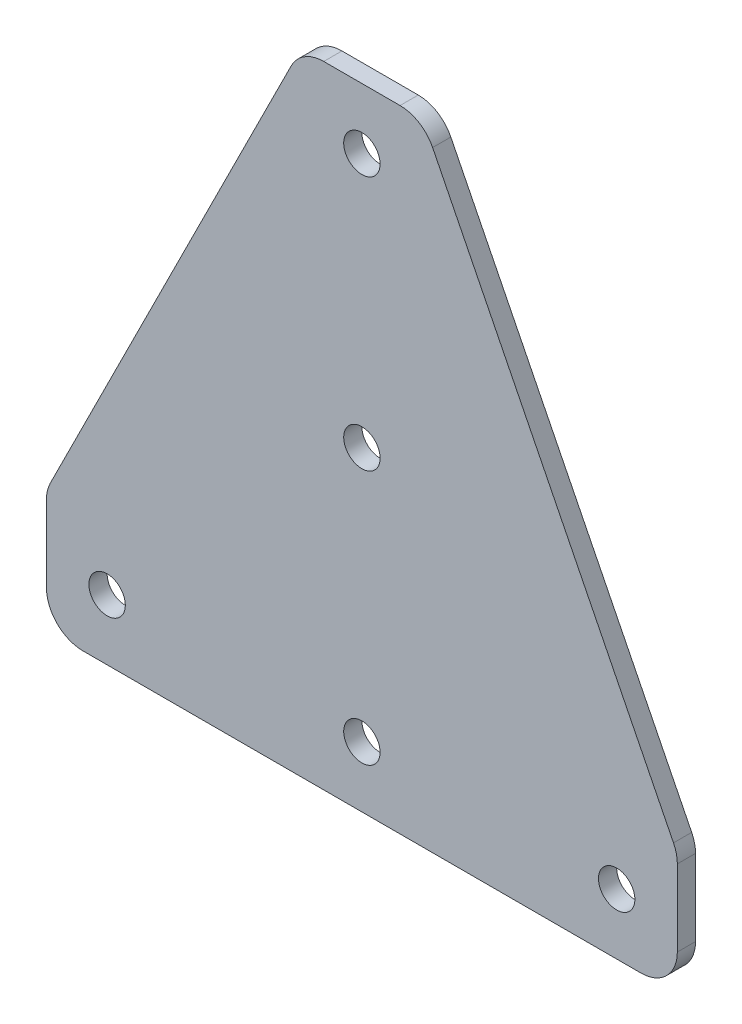
SolidWorks part; units mm, degrees
ref_plane "Plan de face" through (0, 0, 0) normal (0, 0, 1) x (1, 0, 0)
ref_plane "Plan de dessus" through (0, 0, 0) normal (0, 1, 0) x (1, 0, 0)
ref_plane "Plan de droite" through (0, 0, 0) normal (1, 0, 0) x (0, 0, -1)
sketch "Esquisse1" plane through (0, 0, 0) normal (0, 0, 1) x (1, 0, 0)
  line L0 (0, 0) -> (0, 42) construction
  line L1 (-21, 0) -> (21, 0) construction
  line L3 (-26, 47) -> (26, 47)
  line L4 (-26, 47) -> (-26, -5)
  line L5 (-26, -5) -> (26, -5)
  line L6 (26, 47) -> (26, -5)
  circle A0 centre (-21, 0) radius 1.5
  circle A1 centre (0, 0) radius 1.5
  circle A2 centre (21, 0) radius 1.5
  circle A3 centre (0, 42) radius 1.5
  circle A4 centre (0, 21) radius 1.5
  circle A5 centre (-21, 0) radius 5 construction
  point P16 (0, -5)
  dimension "D1" = 3
  dimension "D2" = 42
  dimension "D3" = 52
  dimension "D4" = 5
extrude "Boss.-Extru.1" add sketch "Esquisse1" along normal blind 1.5
sketch "Esquisse2" plane through (0, 0, 1.5) normal (0, 0, 1) x (1, 0, 0)
  line L0 (-26, 47) -> (-5, 47)
  line L1 (26, 47) -> (-26, 47) construction
  line L2 (-5, 47) -> (-26, 5)
  line L3 (-26, 47) -> (-26, -5) construction
  line L4 (-26, 5) -> (-26, 47)
  line L5 (26, 47) -> (26, 5)
  line L6 (26, -5) -> (26, 47) construction
  line L7 (26, 5) -> (5, 47)
  line L8 (5, 47) -> (26, 47)
  line L9 (-26, -5) -> (26, -5) construction
  dimension "D1" = 10
  dimension "D2" = 21
  dimension "D3" = 10
  dimension "D4" = 42
extrude "Enlèv. mat.-Extru.1" cut sketch "Esquisse2" against normal through all
fillet "Congé1" radius 3 6 edges at (-5, 47, 0.75) (26, -5, 0.75) (26, 5, 0.75) (5, 47, 0.75) (-26, 5, 0.75) (-26, -5, 0.75)
